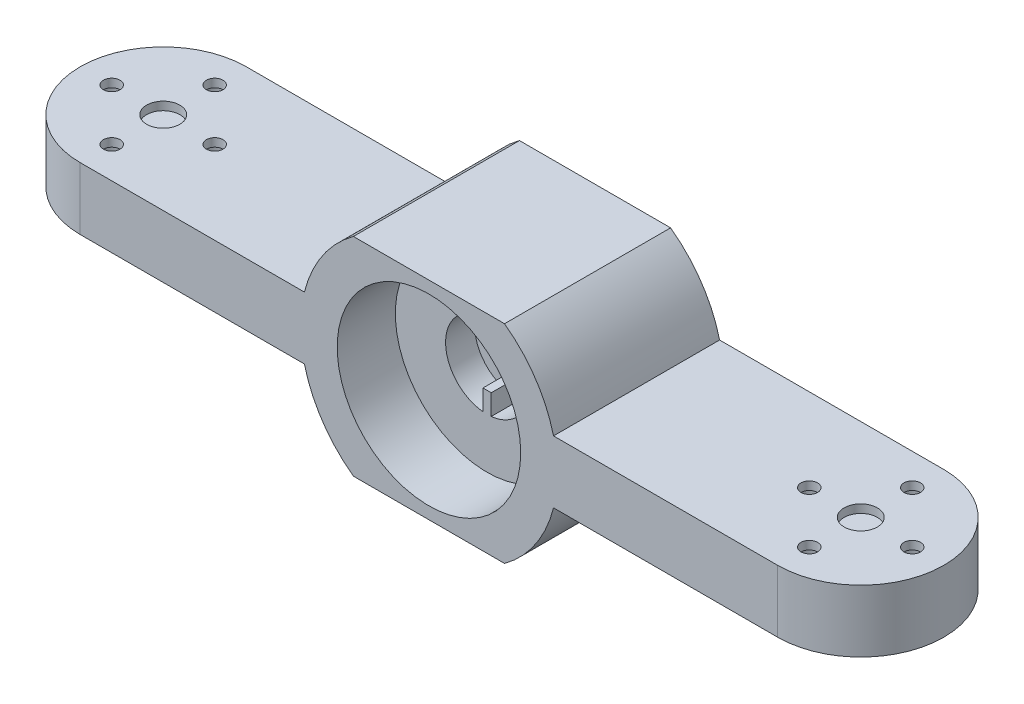
SolidWorks part; units mm, degrees
material "6061 Alloy"
ref_plane "Front Plane" through (0, 0, 0) normal (0, 0, 1) x (1, 0, 0)
ref_plane "Top Plane" through (0, 0, 0) normal (0, 1, 0) x (1, 0, 0)
ref_plane "Right Plane" through (0, 0, 0) normal (1, 0, 0) x (0, 0, -1)
sketch "Sketch1" plane through (0, 0, 0) normal (0, 1, 0) x (1, 0, 0)
  line L1 (-42, -10) -> (42, -10)
  line L3 (-42, 10) -> (42, 10)
  line L5 (-42, -10) -> (42, 10) construction
  line L6 (-42, 10) -> (42, -10) construction
  arc A0 (-42, 10) -> (-42, -10) centre (-42, 0) ccw
  arc A1 (42, -10) -> (42, 10) centre (42, 0) ccw
  point P0 (0, 0)
  point P7 (52, 0)
  dimension "D3" = 10
  dimension "D1" = 84
  dimension "D2" = 20
  dimension "D4" = 10
extrude "Boss-Extrude1" add sketch "Sketch1" along normal blind 25
sketch "Sketch2" plane through (0, 0, 10) normal (0, 0, 1) x (1, 0, 0)
  line L0 (0, 0) -> (0, 12.5) construction
  circle A0 centre (0, 12.5) radius 11.05
  dimension "D2" = 22.1
  dimension "D1" = 12.5
extrude "Cut-Extrude1" cut sketch "Sketch2" against normal blind 7
sketch "Sketch3" plane through (0, 0, 0) normal (0, -1, 0) x (1, 0, 0)
  line L0 (-42, 10) -> (42, 10) construction
  line L2 (15, -10) -> (15, 10)
  line L4 (-15, -10) -> (-15, 10)
  line L5 (15, -10) -> (-15, 10) construction
  line L6 (15, 10) -> (-15, -10) construction
  line L7 (-15, 10) -> (-42, 10)
  line L8 (-42, -10) -> (-15, -10)
  line L9 (15, 10) -> (42, 10)
  line L10 (15, -10) -> (42, -10)
  arc A0 (-42, 10) -> (-42, -10) centre (-42, 0) ccw
  arc A1 (42, -10) -> (42, 10) centre (42, 0) ccw
  point P7 (0, 0)
extrude "Cut-Extrude3" cut sketch "Sketch3" against normal blind 8.75
sketch "Sketch4" plane through (0, 25, 0) normal (0, 1, 0) x (1, 0, 0)
  line L0 (15, -10) -> (15, 10)
  line L1 (-15, -10) -> (-15, 10)
  line L2 (15, -10) -> (-15, 10) construction
  line L3 (15, 10) -> (-15, -10) construction
  line L4 (-15, 10) -> (-55, 10)
  line L5 (-55, -10) -> (-15, -10)
  line L6 (15, 10) -> (55, 10)
  line L7 (15, -10) -> (55, -10)
  arc A0 (-55, 10) -> (-55, -10) centre (-55, 0) ccw
  arc A1 (55, -10) -> (55, 10) centre (55, 0) ccw
  point P2 (0, 0)
  dimension "D1" = 0
  dimension "D2" = 0
extrude "Cut-Extrude5" cut sketch "Sketch4" against normal blind 8.75
sketch "Sketch5" plane through (0, 16.25, 0) normal (0, 1, 0) x (1, 0, 0)
  line L0 (0, 0) -> (-42, 0) construction
  line L1 (-42, 0) -> (-35.8, 0) construction
  line L2 (-42, 0) -> (-42, 6.2) construction
  line L3 (-42, 0) -> (-48.2, 0) construction
  line L4 (-42, 0) -> (-42, -6.2) construction
  line L5 (0, 0) -> (42, 0) construction
  line L6 (42, 0) -> (48.2, 0) construction
  line L7 (42, 0) -> (42, 6.2) construction
  line L8 (42, 0) -> (35.8, 0) construction
  line L9 (42, 0) -> (42, -6.2) construction
  circle A0 centre (-42, 6.2) radius 1
  circle A1 centre (-35.8, 0) radius 1
  circle A2 centre (-42, -6.2) radius 1
  circle A3 centre (-48.2, 0) radius 1
  circle A4 centre (42, 6.2) radius 1
  circle A5 centre (48.2, 0) radius 1
  circle A6 centre (42, -6.2) radius 1
  circle A7 centre (35.8, 0) radius 1
  dimension "D3" = 2
  dimension "D4" = 2
  dimension "D5" = 2
  dimension "D6" = 2
  dimension "D13" = 2
  dimension "D14" = 2
  dimension "D15" = 2
  dimension "D16" = 2
  dimension "D1" = 6.2
  dimension "D2" = 6.2
  dimension "D7" = 6.2
  dimension "D8" = 6.2
  dimension "D9" = 0
  dimension "D10" = 0
  dimension "D11" = 6.2
  dimension "D12" = 6.2
  dimension "D17" = 6.2
  dimension "D18" = 6.2
  dimension "D19" = 0
  dimension "D20" = 0
extrude "Cut-Extrude6" cut sketch "Sketch5" against normal blind 7.5
sketch "Sketch6" plane through (0, 8.75, 0) normal (0, -1, 0) x (1, 0, 0)
  line L0 (0, 0) -> (-42, 0) construction
  line L1 (-42, 0) -> (-35.8, 0) construction
  line L2 (-42, 0) -> (-48.2, 0) construction
  line L3 (-42, 0) -> (-42, 6.2) construction
  line L4 (-42, 0) -> (-42, -6.2) construction
  line L5 (-48.2, 0) -> (-35.8, 0) construction
  line L6 (0, 0) -> (42, 0) construction
  line L7 (42, 0) -> (48.2, 0) construction
  line L8 (42, 0) -> (35.8, 0) construction
  line L9 (42, 0) -> (42, 6.2) construction
  line L10 (42, 0) -> (42, -6.2) construction
  line L11 (35.8, 0) -> (48.2, 0) construction
  circle A0 centre (-42, 6.2) radius 1.95
  circle A1 centre (-35.8, 0) radius 1.95
  circle A2 centre (-48.2, 0) radius 1.95
  circle A3 centre (-42, -6.2) radius 1.95
  circle A4 centre (42, 6.2) radius 1.95
  circle A5 centre (48.2, 0) radius 1.95
  circle A6 centre (35.8, 0) radius 1.95
  circle A7 centre (42, -6.2) radius 1.95
  dimension "D5" = 3.9
  dimension "D6" = 3.9
  dimension "D7" = 3.9
  dimension "D8" = 3.9
  dimension "D15" = 3.9
  dimension "D16" = 3.9
  dimension "D17" = 3.9
  dimension "D18" = 3.9
  dimension "D1" = 6.2
  dimension "D2" = 6.2
  dimension "D3" = 6.2
  dimension "D4" = 6.2
  dimension "D9" = 0
  dimension "D10" = 0
  dimension "D11" = 6.2
  dimension "D12" = 6.2
  dimension "D13" = 6.2
  dimension "D14" = 6.2
  dimension "D19" = 0
  dimension "D20" = 0
  dimension "D21" = 42
extrude "Cut-Extrude7" cut sketch "Sketch6" against normal offset from surface (6.5 mm away) 1 up to face at (-42, 16.25, -5.2)
sketch "Sketch7" plane through (0, 16.25, 0) normal (0, 1, 0) x (1, 0, 0)
  line L0 (0, 0) -> (-42, 0) construction
  line L1 (0, 0) -> (42, 0) construction
  circle A0 centre (-42, 0) radius 2
  circle A1 centre (42, 0) radius 2
  dimension "D1" = 4
  dimension "D2" = 4
extrude "Cut-Extrude8" cut sketch "Sketch7" against normal blind 1
sketch "Sketch8" plane through (0, 0, 10) normal (0, 0, 1) x (1, 0, 0)
  line L0 (0, 0) -> (0, 12.5) construction
  line L1 (-15, 16.25) -> (-15, 25)
  line L2 (15, 0) -> (9.1001, 0)
  line L3 (15, 0) -> (15, 8.75)
  line L4 (15, 25) -> (9.1001, 25)
  line L5 (-15, 0) -> (-15, 8.75)
  line L6 (15, 0) -> (-15, 25) construction
  line L7 (15, 25) -> (-15, 0) construction
  line L8 (-9.1001, 25) -> (-15, 25)
  line L9 (15, 16.25) -> (15, 25)
  line L10 (-9.1001, 0) -> (-15, 0)
  arc A0 (-15, 8.75) -> (-9.1001, 0) centre (0, 12.5) ccw
  arc A1 (-9.1001, 25) -> (-15, 16.25) centre (0, 12.5) ccw
  arc A2 (15, 16.25) -> (9.1001, 25) centre (0, 12.5) ccw
  arc A3 (9.1001, 0) -> (15, 8.75) centre (0, 12.5) ccw
  dimension "D1" = 12.5
extrude "Cut-Extrude9" cut sketch "Sketch8" against normal through all
sketch "Sketch9" plane through (0, 0, 3) normal (0, 0, 1) x (1, 0, 0)
  line L0 (0, 0) -> (0, 12.5) construction
  line L2 (-0.5, 10) -> (0.5, 10)
  line L4 (-0.5, 15) -> (0.5, 15)
  line L6 (-0.5, 10) -> (0.5, 15) construction
  line L7 (-0.5, 15) -> (0.5, 10) construction
  line L8 (0.5, 15) -> (-0.5, 15)
  line L9 (0.5, 15) -> (0.5, 17.4749)
  line L11 (-0.5, 15) -> (-0.5, 17.4749)
  line L12 (0.5, 10) -> (-0.5, 10)
  line L13 (0.5, 10) -> (0.5, 7.5251)
  line L15 (-0.5, 10) -> (-0.5, 7.5251)
  arc A0 (-0.5, 17.4749) -> (-0.5, 7.5251) centre (0, 12.5) ccw
  arc A1 (0.5, 7.5251) -> (0.5, 17.4749) centre (0, 12.5) ccw
  dimension "D1" = 5
  dimension "D3" = 10
  dimension "D2" = 1
  dimension "D4" = 1
  dimension "D5" = 2.4749
extrude "Cut-Extrude10" cut sketch "Sketch9" against normal blind 3.5 contours L13 A1 L9 L4 L11 A0 L15 L2
